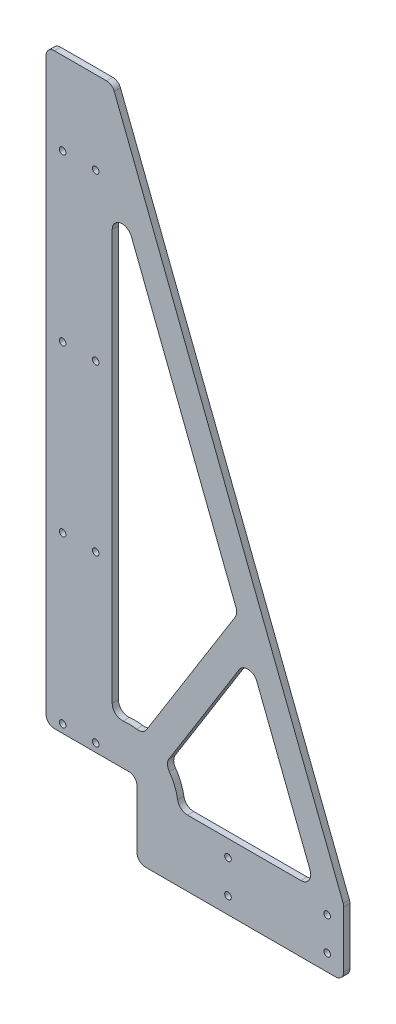
SolidWorks part; units mm, degrees
material "6061-T6 (SS)"
ref_plane "Front Plane" through (0, 0, 0) normal (0, 0, 1) x (1, 0, 0)
ref_plane "Top Plane" through (0, 0, 0) normal (0, 1, 0) x (1, 0, 0)
ref_plane "Right Plane" through (0, 0, 0) normal (1, 0, 0) x (0, 0, -1)
sketch "Sketch1" plane through (0, 0, 0) normal (0, 0, 1) x (1, 0, 0)
  line L0 (69.85, 0) -> (69.85, 57.15)
  line L1 (0, 0) -> (69.85, 0) construction
  line L2 (0, 0) -> (0, 57.15) construction
  line L3 (0, 57.15) -> (69.85, 57.15) construction
  line L4 (69.85, 0) -> (69.85, 57.15) construction
  line L6 (0, 57.15) -> (0, 508)
  line L7 (0, 508) -> (50.8, 508)
  line L8 (50.8, 508) -> (228.6, 50.8)
  line L9 (228.6, 50.8) -> (228.6, 0)
  line L10 (228.6, 0) -> (69.85, 0)
  line L11 (12.7, 63.5) -> (38.1, 63.5) construction
  line L12 (0, 0) -> (50.8, 0) construction
  line L13 (0, 0) -> (0, 508) construction
  line L14 (0, 508) -> (50.8, 508)
  line L15 (50.8, 0) -> (50.8, 508) construction
  line L16 (0, 0) -> (228.6, 0) construction
  line L17 (0, 0) -> (0, 50.8) construction
  line L18 (0, 50.8) -> (228.6, 50.8) construction
  line L19 (228.6, 0) -> (228.6, 50.8) construction
  line L20 (63.5, 38.1) -> (63.5, 12.7) construction
  line L21 (0, 57.15) -> (69.85, 57.15)
  circle A0 centre (12.7, 63.5) radius 2.54
  circle A1 centre (38.1, 63.5) radius 2.54
  circle A2 centre (38.1, 190.5) radius 2.54
  circle A3 centre (12.7, 190.5) radius 2.54
  circle A4 centre (38.1, 317.5) radius 2.54
  circle A5 centre (12.7, 317.5) radius 2.54
  circle A6 centre (63.5, 38.1) radius 2.54
  circle A7 centre (63.5, 12.7) radius 2.54
  circle A8 centre (88.9, 12.7) radius 2.54 construction
  circle A9 centre (88.9, 38.1) radius 2.54 construction
  circle A10 centre (114.3, 12.7) radius 2.54 construction
  circle A11 centre (114.3, 38.1) radius 2.54 construction
  circle A12 centre (139.7, 12.7) radius 2.54
  circle A13 centre (139.7, 38.1) radius 2.54
  circle A14 centre (165.1, 12.7) radius 2.54 construction
  circle A15 centre (165.1, 38.1) radius 2.54 construction
  circle A16 centre (190.5, 12.7) radius 2.54 construction
  circle A17 centre (190.5, 38.1) radius 2.54 construction
  circle A18 centre (88.9, 12.7) radius 2.54 construction
  circle A19 centre (88.9, 38.1) radius 2.54 construction
  circle A20 centre (114.3, 12.7) radius 2.54 construction
  circle A21 centre (114.3, 38.1) radius 2.54 construction
  circle A22 centre (139.7, 12.7) radius 2.54
  circle A23 centre (139.7, 38.1) radius 2.54
  circle A24 centre (165.1, 12.7) radius 2.54 construction
  circle A25 centre (165.1, 38.1) radius 2.54 construction
  circle A26 centre (190.5, 12.7) radius 2.54 construction
  circle A27 centre (190.5, 38.1) radius 2.54 construction
  circle A28 centre (215.9, 12.7) radius 2.54
  circle A29 centre (215.9, 38.1) radius 2.54
  circle A30 centre (38.1, 444.5) radius 2.54
  circle A31 centre (12.7, 444.5) radius 2.54
  point P16 (25.4, 63.5)
  point P28 (63.5, 25.4)
  dimension "D6" = 5.08
  dimension "D14" = 5.08
  dimension "D1" = 57.15
  dimension "D2" = 228.6
  dimension "D3" = 508
  dimension "D4" = 50.8
  dimension "D5" = 50.8
  dimension "D7" = 25.4
  dimension "D8" = 12.7
  dimension "D9" = 25.4
  dimension "D11" = 127
  dimension "D12" = 25.4
  dimension "D13" = 25.4
  dimension "D15" = 12.7
  dimension "D18" = 25.4
  dimension "D19" = 25.4
  dimension "D20" = 69.85
  dimension "D10" = 4
  dimension "D16" = 6
  dimension "D17" = 7
extrude "Boss-Extrude1" add sketch "Sketch1" along normal blind 4.7625 contours L10 L9 L8 L7 L6 L21 L0 A17 A16 A15 A14 A13 A12 A11 A10 A9 A8 A7 A6 A5 A4 A3 A2
fillet "Fillet1" radius 6.35 7 edges at (69.85, 0, 2.3813) (69.85, 57.15, 2.3813) (0, 57.15, 2.3813) (0, 508, 2.3813) (50.8, 508, 2.3813) (228.6, 0, 2.3813) (228.6, 50.8, 2.3813)
sketch "Sketch2" plane through (0, 0, 4.7625) normal (0, 0, 1) x (1, 0, 0)
  line L7 (228.6, 49.6087) -> (228.6, 6.35) construction
  line L8 (228.6, 0) -> (57.15, 0) construction
  line L9 (228.6, 0) -> (228.6, 50.8) construction
  line L10 (228.6, 50.8) -> (57.15, 50.8)
  line L11 (57.15, 0) -> (57.15, 50.8) construction
  line L12 (222.25, 0) -> (76.2, 0) construction
  line L13 (6.35, 508) -> (46.4562, 508) construction
  line L14 (208.28, 20.32) -> (208.28, 46.9879)
  line L15 (90.17, 20.32) -> (208.28, 20.32)
  line L16 (90.17, 50.8) -> (90.17, 20.32)
  line L17 (20.32, 77.47) -> (63.5, 77.47)
  line L18 (20.32, 487.68) -> (20.32, 77.47)
  line L19 (36.8998, 487.68) -> (20.32, 487.68)
  line L20 (208.28, 46.9879) -> (36.8998, 487.68)
  line L21 (208.28, 20.32) -> (208.28, 46.9879)
  line L22 (90.17, 20.32) -> (208.28, 20.32)
  line L23 (90.17, 50.8) -> (90.17, 20.32)
  line L24 (20.32, 77.47) -> (63.5, 77.47)
  line L25 (20.32, 487.68) -> (20.32, 77.47)
  line L26 (36.8998, 487.68) -> (20.32, 487.68)
  line L27 (208.28, 46.9879) -> (36.8998, 487.68)
  line L28 (0, 0) -> (50.8, 0)
  line L29 (0, 0) -> (0, 508)
  line L30 (0, 508) -> (50.8, 508)
  line L31 (50.8, 0) -> (50.8, 508)
  line L32 (63.5, 50.8) -> (170.8368, 222.5748)
  line L40 (72.1162, 45.416) -> (173.9459, 208.3776)
  line L41 (54.8838, 56.184) -> (156.7135, 219.1456)
  line L42 (63.5, 50.8) -> (165.3297, 213.7616) construction
  line L47 (82.55, 50.8) -> (82.55, 12.7)
  line L48 (82.55, 12.7) -> (215.9, 12.7)
  line L49 (215.9, 12.7) -> (215.9, 48.4175)
  line L50 (215.9, 48.4175) -> (42.1123, 495.3)
  line L51 (42.1123, 495.3) -> (12.7, 495.3)
  line L52 (12.7, 495.3) -> (12.7, 69.85)
  line L53 (12.7, 69.85) -> (63.5, 69.85)
  line L54 (82.55, 50.8) -> (82.55, 12.7)
  line L55 (82.55, 12.7) -> (215.9, 12.7)
  line L56 (215.9, 12.7) -> (215.9, 48.4175)
  line L57 (215.9, 48.4175) -> (42.1123, 495.3)
  line L58 (42.1123, 495.3) -> (12.7, 495.3)
  line L59 (12.7, 495.3) -> (12.7, 69.85)
  line L60 (12.7, 69.85) -> (63.5, 69.85)
  arc A7 (90.17, 50.8) -> (63.5, 77.47) centre (63.5, 50.8) ccw
  arc A8 (90.17, 50.8) -> (63.5, 77.47) centre (63.5, 50.8) ccw
  arc A16 (50.8, 86.721) -> (101.6, 50.8) centre (63.5, 50.8) cw
  arc A23 (82.55, 50.8) -> (63.5, 69.85) centre (63.5, 50.8) ccw
  arc A24 (82.55, 50.8) -> (63.5, 69.85) centre (63.5, 50.8) ccw
  dimension "D8" = 38.1
  dimension "D2" = 50.8
  dimension "D3" = 50.8
  dimension "D4" = 58
  dimension "D1" = 20.32
  dimension "D5" = 12.7
  dimension "D6" = 10.16
  dimension "D7" = 10.16
extrude "Cut-Extrude1" cut sketch "Sketch2" against normal through all contours A8 L10 L27 L40 | A8 L41 L27 L31
fillet "Fillet2" radius 7.62 8 edges at (156.4228, 180.3349, 2.3813) (206.7975, 50.8, 2.3813) (101.6, 50.8, 2.3813) (91.575, 76.5566, 2.3813) (50.8, 451.9365, 2.3813) (147.2312, 203.9706, 2.3813) (50.8, 86.721, 2.3813) (74.3427, 87.3246, 2.3813)
sketch "Sketch3" plane through (0, 0, 4.7625) normal (0, 0, 1) x (1, 0, 0)
  line L0 (-12.7, 23.5478) -> (-12.7, 50023.5478) construction
  line L1 (-12.7, -12.7) -> (49987.3, -12.7) construction
  line L2 (0, 63.5) -> (0, 501.65) construction
  line L3 (222.25, 0) -> (76.2, 0) construction
  circle A0 centre (65.3018, 369.6548) radius 8.419
  circle A1 centre (127.0944, 203.2239) radius 6.7831
  circle A2 centre (65.3018, 106.934) radius 8.6199
  circle A3 centre (154.1053, 144.2168) radius 9.2725
  circle A4 centre (114.2207, 68.6392) radius 4.2148
  circle A5 centre (181.1161, 72.5653) radius 9.4151
  circle A6 centre (122.1658, 297.949) radius 4.9286
  circle A7 centre (188.7513, 121.4569) radius 4.1626
  point P4 (-12.7, -12.7)
  point P25 (65.3018, 108.1237)
  point P26 (114.2207, 68.6392)
  point P27 (65.3018, 106.934)
  dimension "D1" = 12.7
  dimension "D2" = 12.7
